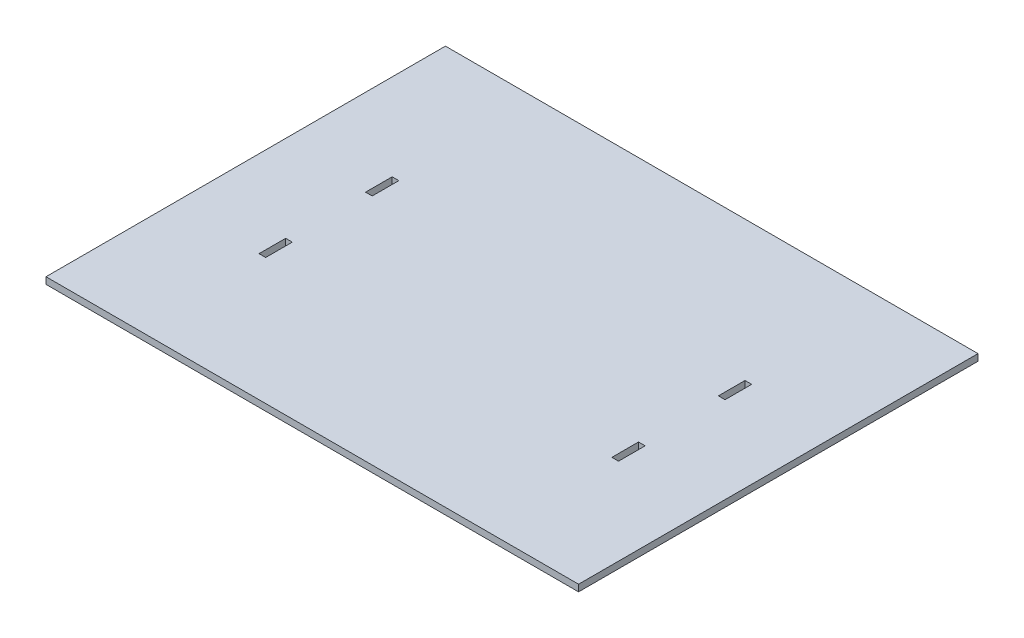
SolidWorks part; units mm, degrees
ref_plane "前基準面" through (0, 0, 0) normal (0, 0, 1) x (1, 0, 0)
ref_plane "上基準面" through (0, 0, 0) normal (0, 1, 0) x (1, 0, 0)
ref_plane "右基準面" through (0, 0, 0) normal (1, 0, 0) x (0, 0, -1)
sketch "草圖1" plane through (0, 0, 0) normal (0, 1, 0) x (1, 0, 0)
  line L0 (135, -150) -> (130, -150) construction
  line L1 (200, 150) -> (-200, 150)
  line L2 (200, 150) -> (200, -150)
  line L3 (200, -150) -> (-200, -150)
  line L4 (-200, 150) -> (-200, -150)
  line L5 (0, -150) -> (0, 150) construction
  line L6 (200, 0) -> (-200, 0) construction
  line L7 (-135, 150) -> (-130, 150) construction
  line L8 (-135, 150) -> (-135, -150) construction
  line L9 (-135, -150) -> (-130, -150) construction
  line L10 (-130, 150) -> (-130, -150) construction
  line L11 (130, 150) -> (130, -150) construction
  line L12 (135, 150) -> (130, 150) construction
  line L13 (135, 150) -> (135, -150) construction
  line L15 (-135, 45) -> (-130, 45)
  line L16 (-135, 45) -> (-135, 25)
  line L17 (-135, 25) -> (-130, 25)
  line L18 (-130, 45) -> (-130, 25)
  line L19 (-135, -35) -> (-130, -35)
  line L20 (-135, -35) -> (-135, -55)
  line L21 (-135, -55) -> (-130, -55)
  line L22 (-130, -35) -> (-130, -55)
  line L23 (130, 45) -> (135, 45)
  line L24 (130, 45) -> (130, 25)
  line L25 (130, 25) -> (135, 25)
  line L26 (135, 45) -> (135, 25)
  line L27 (130, -35) -> (135, -35)
  line L28 (130, -35) -> (130, -55)
  line L29 (130, -55) -> (135, -55)
  line L30 (135, -35) -> (135, -55)
  point P0 (0, 0)
  dimension "D1" = 400
  dimension "D2" = 270
  dimension "D3" = 5
  dimension "D4" = 300
  dimension "D5" = 60
  dimension "D6" = 105
  dimension "D7" = 20
extrude "填料-伸長1" add sketch "草圖1" along normal blind 5
